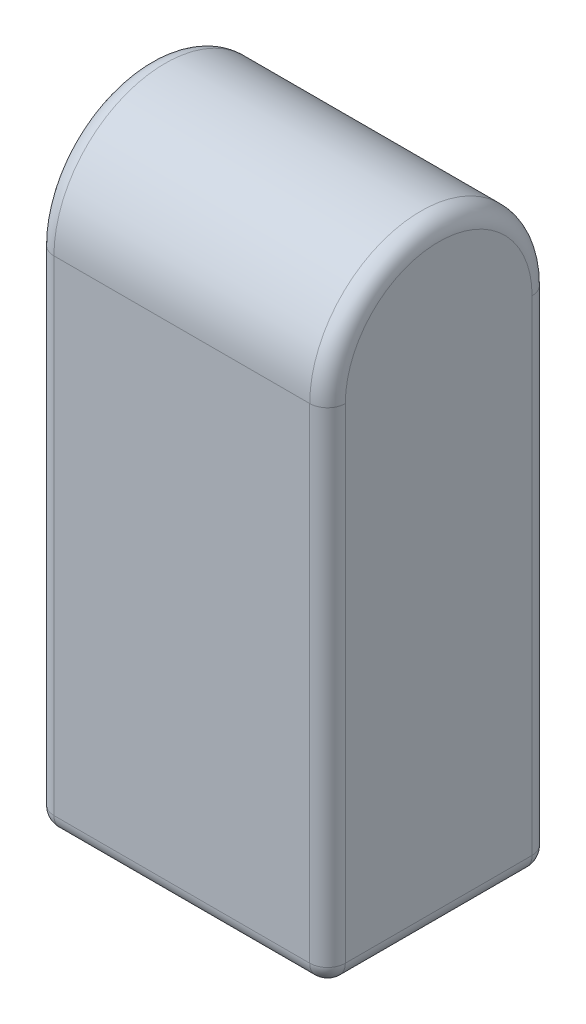
SolidWorks part; units mm, degrees
ref_plane "Front Plane" through (0, 0, 0) normal (0, 0, 1) x (1, 0, 0)
ref_plane "Top Plane" through (0, 0, 0) normal (0, 1, 0) x (1, 0, 0)
ref_plane "Right Plane" through (0, 0, 0) normal (1, 0, 0) x (0, 0, -1)
sketch "Sketch1" plane through (0, 0, 0) normal (1, 0, 0) x (0, 0, -1)
  line L0 (-12.5, 56.5) -> (-12.5, 0)
  line L1 (-12.5, 0) -> (12.5, 0)
  line L2 (12.5, 0) -> (12.5, 56.5)
  arc A0 (-12.5, 56.5) -> (12.5, 56.5) centre (0, 56.5) cw
  point P6 (0, 0)
  point P8 (0, 69)
  dimension "D1" = 69
  dimension "D2" = 25
extrude "Boss-Extrude1" add sketch "Sketch1" along normal mid plane 32.766
fillet "Fillet1" radius 2 10 edges at (-16.383, 28.25, -12.5) (-16.383, 28.25, 12.5) (16.383, 28.25, -12.5) (16.383, 28.25, 12.5) (0, 0, 12.5) (16.383, 0, 0) (0, 0, -12.5) (-16.383, 0, 0) (-16.383, 69, 0) (16.383, 69, 0)
